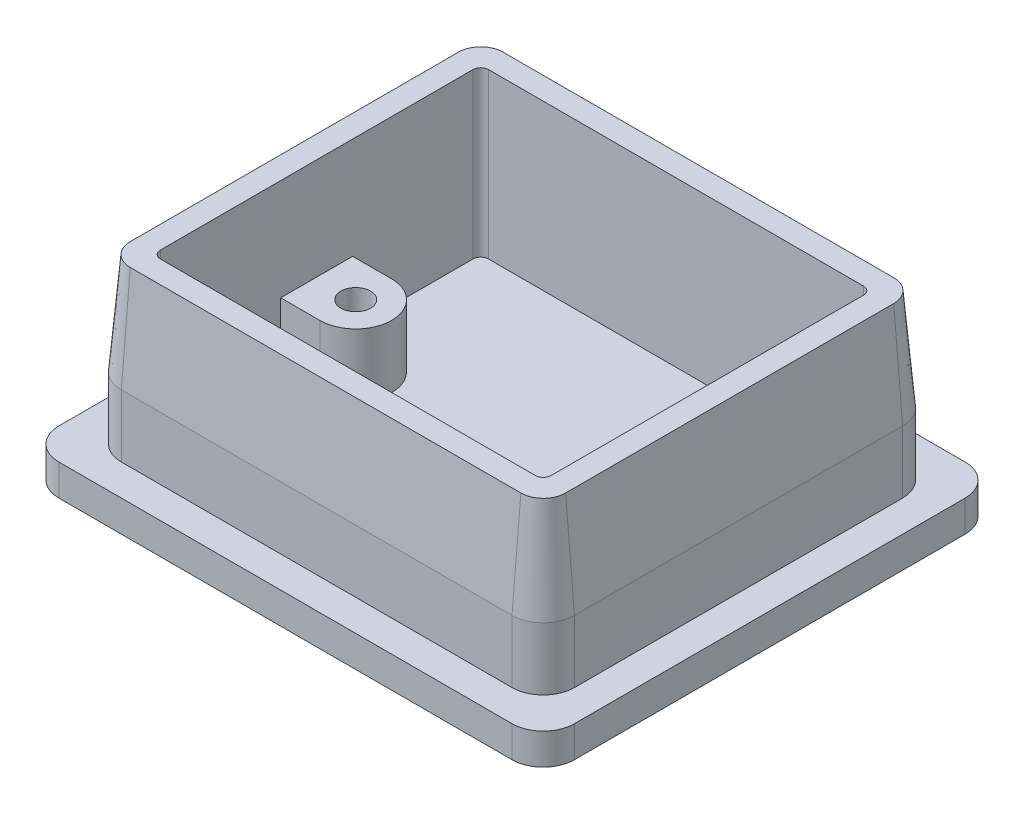
SolidWorks part; units mm, degrees
ref_plane "Front Plane" through (0, 0, 0) normal (0, 0, 1) x (1, 0, 0)
ref_plane "Top Plane" through (0, 0, 0) normal (0, 1, 0) x (1, 0, 0)
ref_plane "Right Plane" through (0, 0, 0) normal (1, 0, 0) x (0, 0, -1)
sketch "Sketch1" plane through (0, 0, 0) normal (0, 1, 0) x (1, 0, 0)
  line L1 (-16.5, -14.5) -> (16.5, -14.5)
  line L2 (-16.5, -14.5) -> (-16.5, 14.5)
  line L3 (-16.5, 14.5) -> (16.5, 14.5)
  line L4 (16.5, -14.5) -> (16.5, 14.5)
  line L5 (-16.5, -14.5) -> (16.5, 14.5) construction
  line L6 (-16.5, 14.5) -> (16.5, -14.5) construction
  point P0 (0, 0)
  dimension "D1" = 33
  dimension "D2" = 29
extrude "Boss-Extrude1" add sketch "Sketch1" along normal blind 2
sketch "Sketch2" plane through (0, 2, 0) normal (0, 1, 0) x (1, 0, 0)
  line L0 (16.5, 14.5) -> (-16.5, 14.5) construction
  line L1 (-14.5, -12.5) -> (14.5, -12.5)
  line L2 (-14.5, -12.5) -> (-14.5, 12.5)
  line L3 (-14.5, 12.5) -> (14.5, 12.5)
  line L4 (14.5, -12.5) -> (14.5, 12.5)
  line L5 (-14.5, -12.5) -> (14.5, 12.5) construction
  line L6 (-14.5, 12.5) -> (14.5, -12.5) construction
  line L7 (-16.5, 14.5) -> (-16.5, -14.5) construction
  line L9 (-12.5, -10.5) -> (12.5, -10.5)
  line L10 (-12.5, -10.5) -> (-12.5, 10.5)
  line L11 (-12.5, 10.5) -> (12.5, 10.5)
  line L12 (12.5, -10.5) -> (12.5, 10.5)
  line L13 (-12.5, -10.5) -> (12.5, 10.5) construction
  line L14 (-12.5, 10.5) -> (12.5, -10.5) construction
  point P0 (0, 0)
  point P10 (0, 0)
  dimension "D1" = 2
  dimension "D2" = 2
  dimension "D3" = 2
  dimension "D4" = 2
extrude "Boss-Extrude2" add sketch "Sketch2" along normal blind 10.5
sketch "Sketch3" plane through (0, 2, 0) normal (0, 1, 0) x (1, 0, 0)
  line L0 (0, 14.5) -> (0, -14.5) construction
  line L5 (-12.5, -10.5) -> (12.5, -10.5) construction
  line L6 (-5.25, -9.5) -> (5.25, -9.5)
  line L7 (16.5, 14.5) -> (-16.5, 14.5) construction
  line L8 (-16.5, -14.5) -> (16.5, -14.5) construction
  line L9 (-5.25, -9.5) -> (-5.25, -3.5)
  line L10 (-5.25, -3.5) -> (5.25, -3.5)
  line L11 (5.25, -9.5) -> (5.25, -3.5)
  line L12 (-5.25, -9.5) -> (5.25, -3.5) construction
  line L13 (-5.25, -3.5) -> (5.25, -9.5) construction
  point P0 (0, -6.5)
  dimension "D1" = 1
  dimension "D2" = 6
  dimension "D3" = 10.5
extrude "Cut-Extrude1" cut sketch "Sketch3" against normal up to surface (2 mm away) up to face at (0, 0, 0)
sketch "Sketch4" plane through (0, 2, 0) normal (0, 1, 0) x (1, 0, 0)
  line L0 (12.5, 10.5) -> (-12.5, 10.5) construction
  line L1 (12.5, -10.5) -> (12.5, 10.5) construction
  circle A0 centre (6.5, 4.5) radius 2.25
  dimension "D1" = 4.5
  dimension "D2" = 6
  dimension "D3" = 6
extrude "Cut-Extrude2" cut sketch "Sketch4" against normal up to surface (2 mm away) up to face at (0, 0, 6.5)
sketch "Sketch5" plane through (0, 2, 0) normal (0, 1, 0) x (1, 0, 0)
  line L0 (-16.5, 0) -> (16.5, 0) construction
  line L3 (-16.5, 14.5) -> (-16.5, -14.5) construction
  line L4 (16.5, -14.5) -> (16.5, 14.5) construction
  line L5 (-12.5, 10.5) -> (-12.5, -10.5) construction
  line L6 (-10, 2.3) -> (-12.5, 2.3)
  line L7 (-12.5, 2.3) -> (-12.5, -2.3)
  line L8 (-12.5, -2.3) -> (-10, -2.3)
  circle A0 centre (-10, 0) radius 0.95
  arc A1 (-10, -2.3) -> (-10, 2.3) centre (-10, 0) ccw
  dimension "D1" = 1.9
  dimension "D3" = 4.6
  dimension "D2" = 2.5
extrude "Boss-Extrude3" add sketch "Sketch5" along normal blind 4
mirror "Mirror1" about plane through (0, 0, 0) normal (1, 0, 0) of "Boss-Extrude3"
fillet "Fillet1" radius 2 8 edges at (-14.5, 7.25, -12.5) (-14.5, 7.25, 12.5) (14.5, 7.25, 12.5) (14.5, 7.25, -12.5) (16.5, 1, -14.5) (-16.5, 1, -14.5) (16.5, 1, 14.5) (-16.5, 1, 14.5)
fillet "Fillet2" radius 0.5 8 edges at (-5.25, 1, 9.5) (-5.25, 1, 3.5) (5.25, 1, 3.5) (5.25, 1, 9.5) (-12.5, 7.25, 10.5) (12.5, 7.25, 10.5) (12.5, 7.25, -10.5) (-12.5, 7.25, -10.5)
chamfer "Chamfer1" distance 6.5 angle 5 8 edges at (0, 12.5, 12.5) (13.9142, 12.5, 11.9142) (-13.9142, 12.5, 11.9142) (14.5, 12.5, 0) (-14.5, 12.5, 0) (13.9142, 12.5, -11.9142) (-13.9142, 12.5, -11.9142) (0, 12.5, -12.5)
